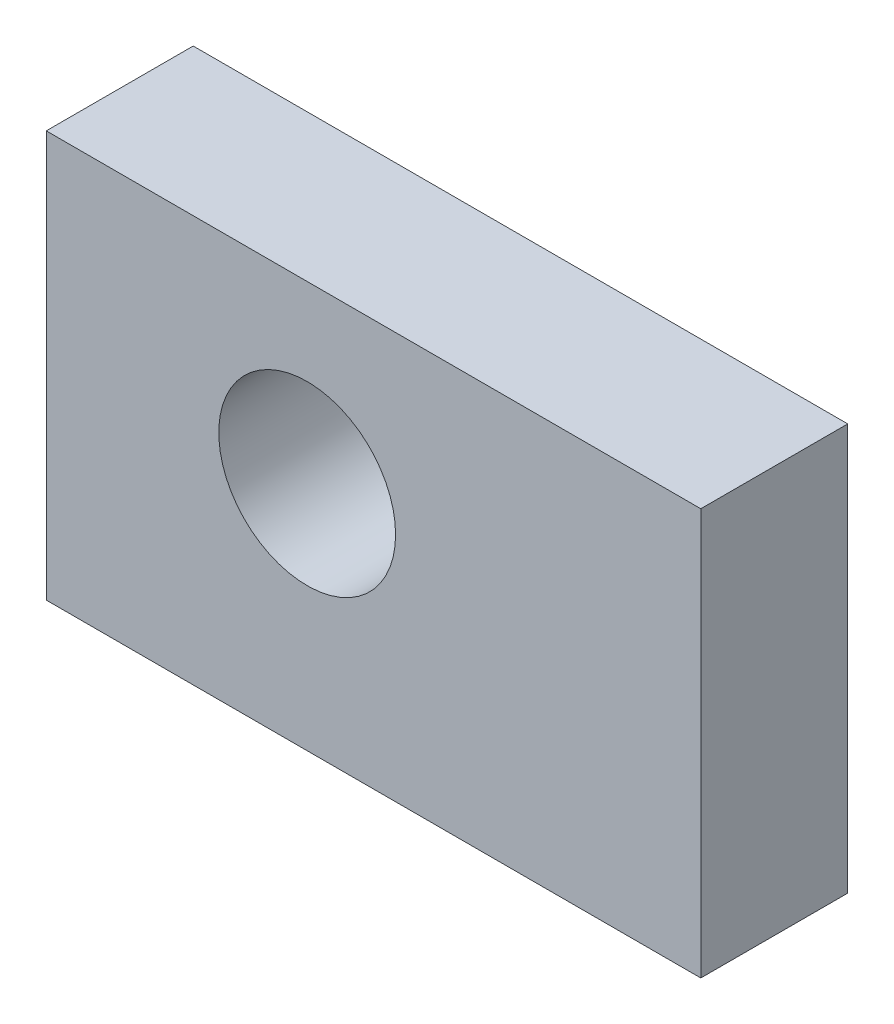
SolidWorks part; units mm, degrees
ref_plane "Alzado" through (0, 0, 0) normal (0, 0, 1) x (1, 0, 0)
ref_plane "Planta" through (0, 0, 0) normal (0, 1, 0) x (1, 0, 0)
ref_plane "Vista lateral" through (0, 0, 0) normal (1, 0, 0) x (0, 0, -1)
sketch "Croquis1" plane through (0, 0, 0) normal (0, 0, 1) x (1, 0, 0)
  line L1 (0, 0) -> (44.5396, 0)
  line L2 (0, 0) -> (0, 27.6546)
  line L3 (0, 27.6546) -> (44.5396, 27.6546)
  line L4 (44.5396, 0) -> (44.5396, 27.6546)
  dimension "D1" = 44.5396
  dimension "D2" = 27.6546
extrude "Saliente-Extruir1" add sketch "Croquis1" along normal blind 10
sketch "Croquis2" plane through (0, 0, 10) normal (0, 0, 1) x (1, 0, 0)
  line L0 (0, 27.6546) -> (0, 0) construction
  line L1 (44.5396, 27.6546) -> (0, 27.6546) construction
  circle A0 centre (17.7551, 15.7445) radius 6.0163
  dimension "D1" = 17.7551
  dimension "D3" = 12.0325
  dimension "D2" = 11.9101
extrude "Cortar-Extruir1" cut sketch "Croquis2" against normal blind 10
